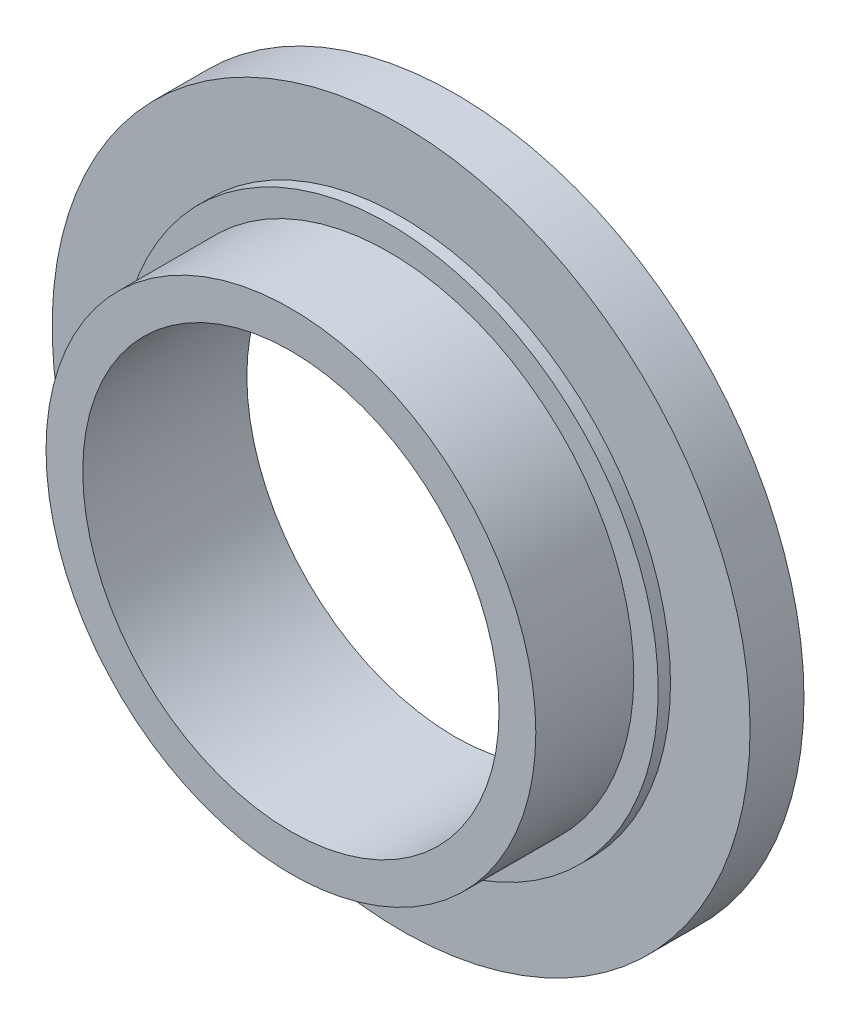
SolidWorks part; units mm, degrees
ref_plane "Front Plane" through (0, 0, 0) normal (0, 0, 1) x (1, 0, 0)
ref_plane "Top Plane" through (0, 0, 0) normal (0, 1, 0) x (1, 0, 0)
ref_plane "Right Plane" through (0, 0, 0) normal (1, 0, 0) x (0, 0, -1)
sketch "Sketch1" plane through (0, 0, 0) normal (0, 0, 1) x (1, 0, 0)
  circle A0 centre (0, 0) radius 14.25
  dimension "D1" = 28.5
extrude "Extrude1" add sketch "Sketch1" along normal blind 2.2
sketch "Sketch2" plane through (0, 0, 2.2) normal (0, 0, 1) x (1, 0, 0)
  circle A0 centre (0, 0) radius 11
  dimension "D1" = 22
extrude "Extrude2" add sketch "Sketch2" along normal blind 0.5
sketch "Sketch3" plane through (0, 0, 2.7) normal (0, 0, 1) x (1, 0, 0)
  circle A0 centre (0, 0) radius 10
  dimension "D1" = 20
extrude "Extrude3" add sketch "Sketch3" along normal blind 4
sketch "Sketch4" plane through (0, 0, 6.7) normal (0, 0, 1) x (1, 0, 0)
  circle A0 centre (0, 0) radius 8.5
  dimension "D1" = 17
extrude "Cut-Extrude1" cut sketch "Sketch4" against normal through all
